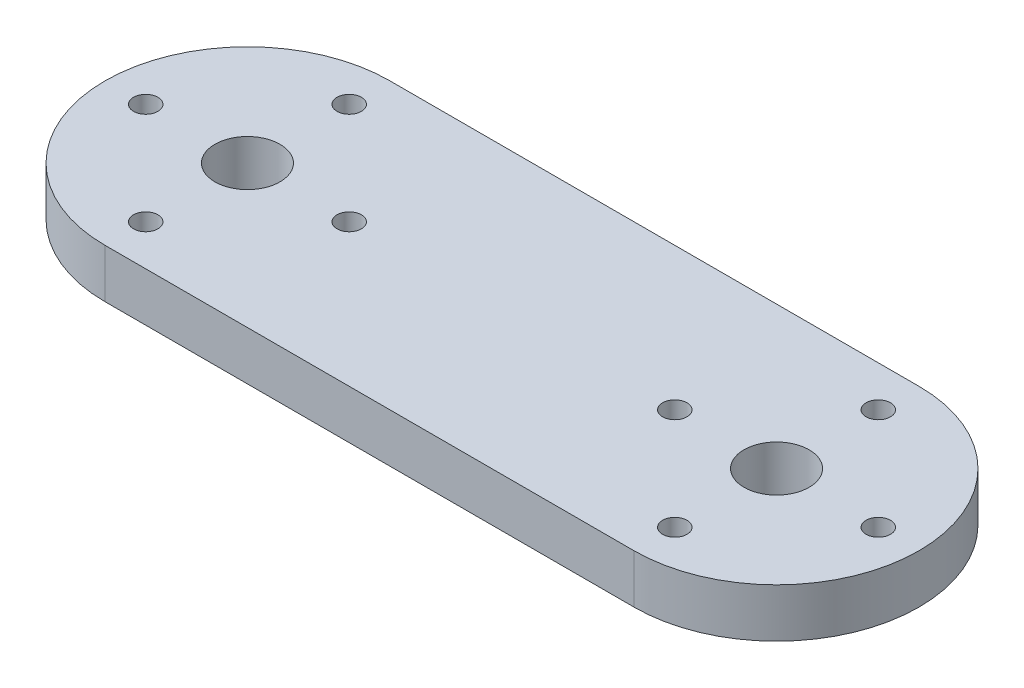
SolidWorks part; units mm, degrees
material "Pine"
ref_plane "Front Plane" through (0, 0, 0) normal (0, 0, 1) x (1, 0, 0)
ref_plane "Top Plane" through (0, 0, 0) normal (0, 1, 0) x (1, 0, 0)
ref_plane "Right Plane" through (0, 0, 0) normal (1, 0, 0) x (0, 0, -1)
sketch "Sketch1" plane through (0, 0, 0) normal (0, 1, 0) x (1, 0, 0)
  line L0 (0, 0) -> (65, 0) construction
  line L2 (0, 17.5) -> (65, 17.5)
  line L3 (0, -17.5) -> (65, -17.5)
  arc A0 (0, 17.5) -> (0, -17.5) centre (0, 0) ccw
  arc A1 (65, -17.5) -> (65, 17.5) centre (65, 0) ccw
  circle A2 centre (65, 0) radius 4
  circle A3 centre (0, 0) radius 4
  circle A4 centre (65, 0) radius 22.25
  circle A5 centre (0, 0) radius 20
  circle A6 centre (65, 0) radius 17.25
  point P5 (32.5, 0)
  dimension "D2" = 17.5
  dimension "D3" = 8
  dimension "D4" = 8
  dimension "D5" = 5
  dimension "D6" = 40
  dimension "D7" = 34.5
  dimension "D1" = 65
extrude "Boss-Extrude1" add sketch "Sketch1" along normal blind 6
sketch "Sketch3" plane through (0, 6, 0) normal (0, 1, 0) x (1, 0, 0)
  circle A0 centre (0, 0) radius 12.5
  circle A1 centre (0, 12.5) radius 1.5
  circle A2 centre (12.5, 0) radius 1.5
  circle A3 centre (0, -12.5) radius 1.5
  circle A4 centre (-12.5, 0) radius 1.5
  dimension "D1" = 25
  dimension "D2" = 3
  dimension "D3" = 4
extrude "Cut-Extrude1" cut sketch "Sketch3" against normal blind 19 contours A1 | A4 | A2 | A3
sketch "Sketch4" plane through (0, 6, 0) normal (0, 1, 0) x (1, 0, 0)
  circle A0 centre (65, 0) radius 12.5
  circle A3 centre (77.5, 0) radius 1.5
  circle A4 centre (65, -12.5) radius 1.5
  circle A5 centre (52.5, 0) radius 1.5
  circle A6 centre (65, 12.5) radius 1.5
  dimension "D1" = 25
  dimension "D2" = 4
  dimension "D3" = 3
extrude "Cut-Extrude2" cut sketch "Sketch4" against normal blind 19 contours A3 | A6 | A5 | A4
